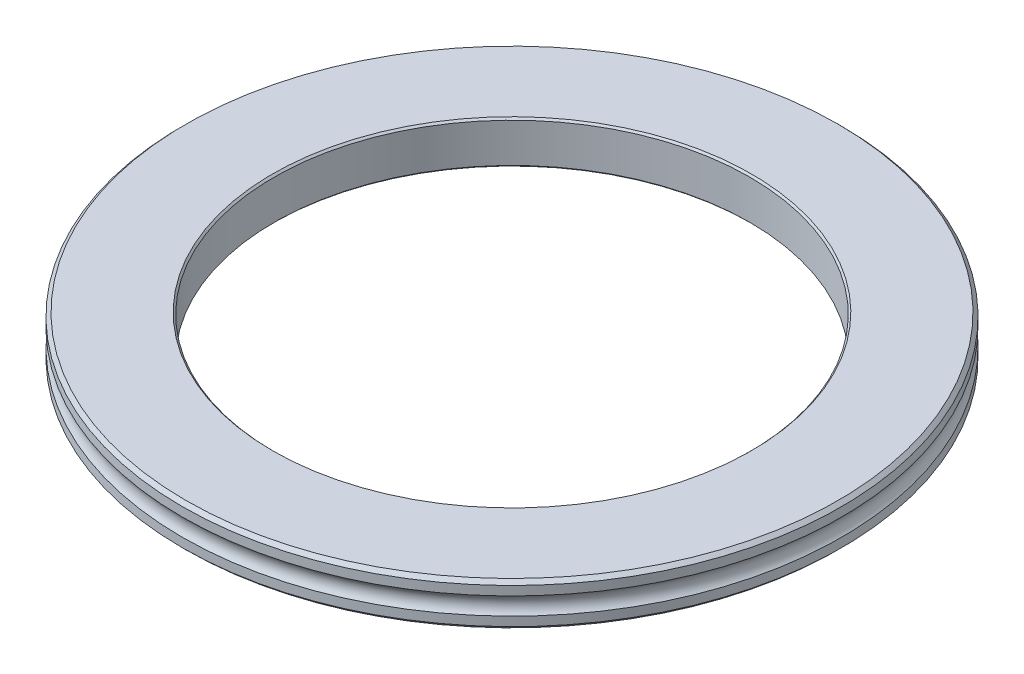
SolidWorks part; units mm, degrees
ref_plane "前基準面" through (0, 0, 0) normal (0, 0, 1) x (1, 0, 0)
ref_plane "上基準面" through (0, 0, 0) normal (0, 1, 0) x (1, 0, 0)
ref_plane "右基準面" through (0, 0, 0) normal (1, 0, 0) x (0, 0, -1)
sketch "草圖1" plane through (0, 0, 0) normal (0, 0, 1) x (1, 0, 0)
  line L0 (92.5, 6) -> (0, 6)
  line L1 (0, 6) -> (0, -6)
  line L2 (0, -6) -> (92.5, -6)
  line L3 (92.5, -6) -> (92.5, -2.4495)
  line L4 (92.5, 2.4495) -> (92.5, 6)
  line L5 (0, 6) -> (0, -6) construction
  arc A0 (92.5, -2.4495) -> (92.5, 2.4495) centre (95, 0) cw
revolve "旋轉1" add sketch "草圖1" angle 360 about L5
hole_wizard "鑽孔2" positions "草圖5" profile "草圖4" legacy
sketch "草圖5" plane through (0, -6, 0) normal (0, -1, 0) x (-1, 0, 0)
  point P0 (0, 0)
sketch "草圖4" plane through (0, -6, 0) normal (1, 0, 0) x (0, 0, -1)
  line L0 (0, 0) -> (0, 12)
  line L1 (0, 12) -> (66.75, 12)
  line L2 (66.75, 12) -> (66.75, 0)
  line L3 (66.75, 0) -> (0, 0)
  line L4 (0, 110) -> (0, -10) construction
  dimension "直徑" = 133.5
  dimension "深度" = 12
chamfer "導角1" distance 0.5 angle 45 2 edges at (0, 6, -66.75) (0, -6, -66.75)
chamfer "導角2" distance 1 angle 45 2 edges at (0, 6, -92.5) (0, -6, -92.5)
